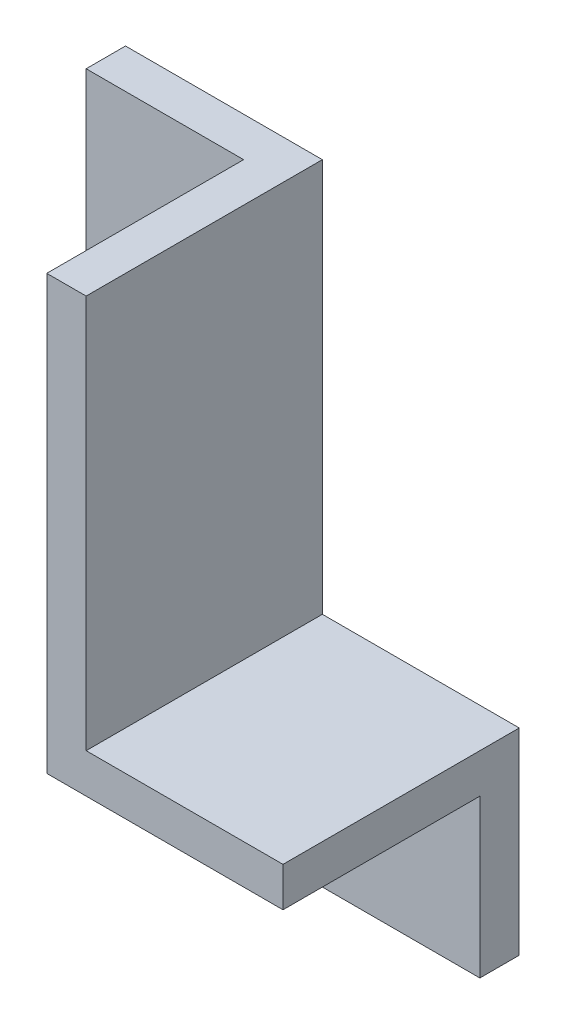
SolidWorks part; units mm, degrees
ref_plane "Front Plane" through (0, 0, 0) normal (0, 0, 1) x (1, 0, 0)
ref_plane "Top Plane" through (0, 0, 0) normal (0, 1, 0) x (1, 0, 0)
ref_plane "Right Plane" through (0, 0, 0) normal (1, 0, 0) x (0, 0, -1)
sketch "Sketch1" plane through (0, 0, 0) normal (0, 0, 1) x (1, 0, 0)
  line L0 (0, 150) -> (50, 150)
  line L1 (0, 0) -> (100, 0)
  line L2 (0, 0) -> (0, 150)
  line L3 (100, 50) -> (100, 0)
  line L5 (50, 150) -> (50, 50)
  line L6 (50, 50) -> (100, 50)
  dimension "D1" = 150
extrude "Boss-Extrude1" add sketch "Sketch1" along normal blind 10
sketch "Sketch2" plane through (0, 0, 10) normal (0, 0, 1) x (1, 0, 0)
  line L0 (40, 150) -> (40, 40)
  line L1 (50, 150) -> (0, 150) construction
  line L2 (40, 40) -> (100, 40)
  line L3 (100, 0) -> (100, 50) construction
  line L4 (100, 40) -> (100, 50)
  line L5 (100, 50) -> (50, 50)
  line L6 (50, 50) -> (50, 150)
  line L7 (50, 150) -> (40, 150)
  dimension "D1" = 10
  dimension "D2" = 10
extrude "Boss-Extrude2" add sketch "Sketch2" along normal blind 50
